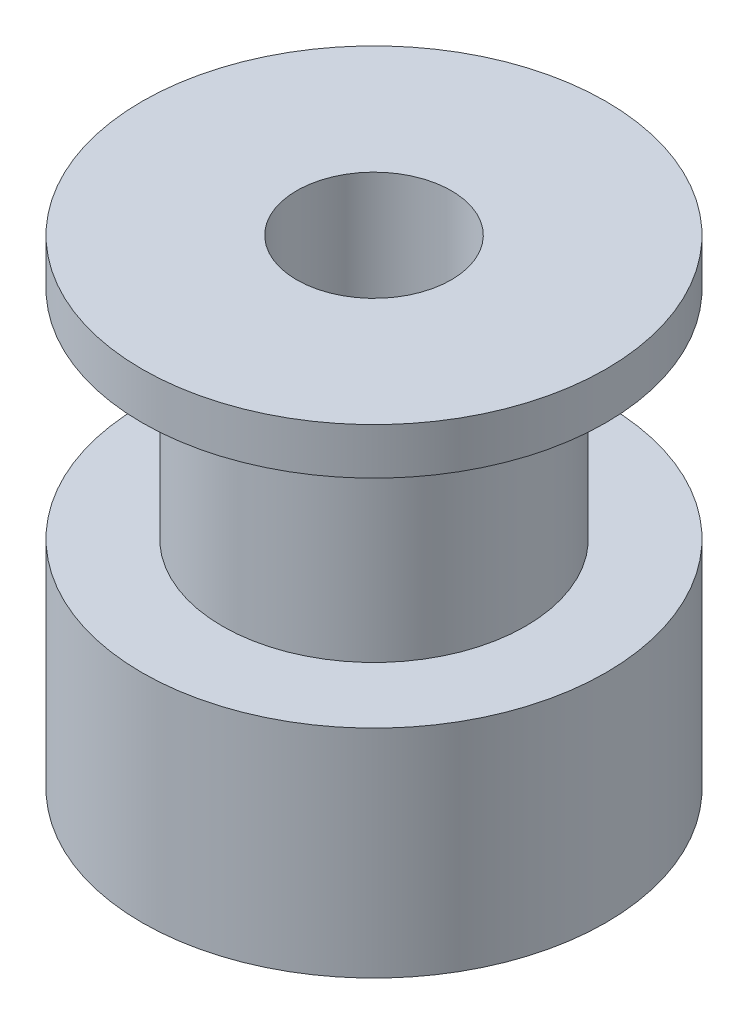
SolidWorks part; units mm, degrees
ref_plane "Front Plane" through (0, 0, 0) normal (0, 0, 1) x (1, 0, 0)
ref_plane "Top Plane" through (0, 0, 0) normal (0, 1, 0) x (1, 0, 0)
ref_plane "Right Plane" through (0, 0, 0) normal (1, 0, 0) x (0, 0, -1)
sketch "Sketch1" plane through (0, 0, 0) normal (0, 1, 0) x (1, 0, 0)
  circle A0 centre (0, 0) radius 7.5
  dimension "D1" = 15
extrude "Boss-Extrude1" add sketch "Sketch1" along normal blind 7
sketch "Sketch2" plane through (0, 7, 0) normal (0, 1, 0) x (1, 0, 0)
  circle A0 centre (0, 0) radius 4.9
  dimension "D1" = 9.8
extrude "Boss-Extrude2" add sketch "Sketch2" along normal blind 7
sketch "Sketch3" plane through (0, 14, 0) normal (0, 1, 0) x (1, 0, 0)
  circle A0 centre (0, 0) radius 7.5
extrude "Boss-Extrude3" add sketch "Sketch3" along normal blind 1.5
sketch "Sketch4" plane through (0, 15.5, 0) normal (0, 1, 0) x (1, 0, 0)
  circle A0 centre (0, 0) radius 2.5
  dimension "D1" = 5
extrude "Cut-Extrude1" cut sketch "Sketch4" against normal through all
